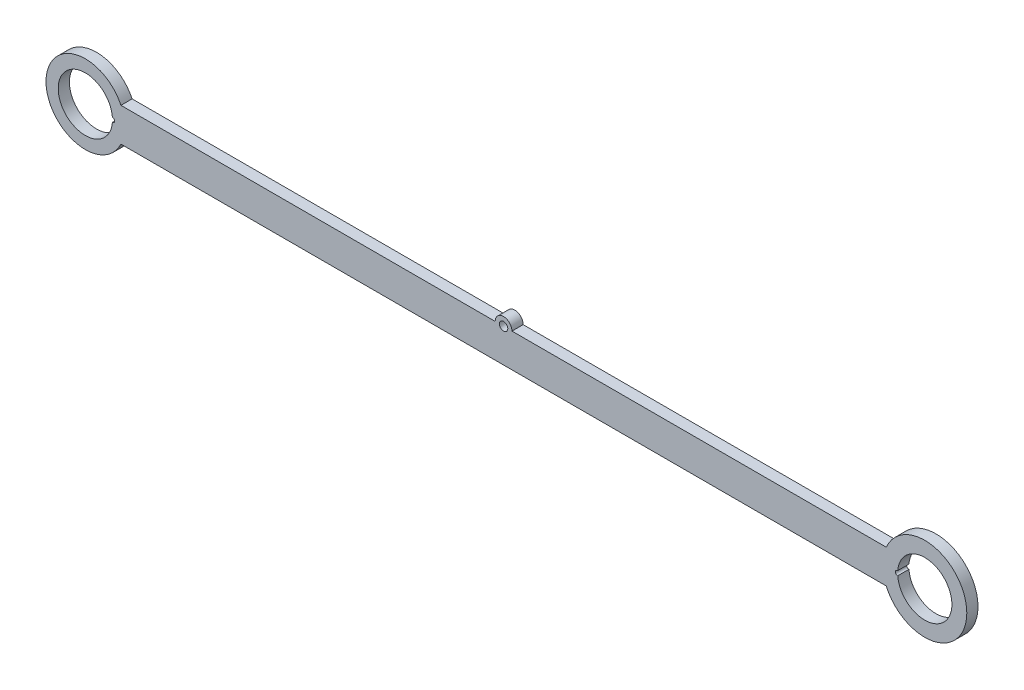
SolidWorks part; units mm, degrees
ref_plane "前视基准面" through (0, 0, 0) normal (0, 0, 1) x (1, 0, 0)
ref_plane "上视基准面" through (0, 0, 0) normal (0, 1, 0) x (1, 0, 0)
ref_plane "右视基准面" through (0, 0, 0) normal (1, 0, 0) x (0, 0, -1)
sketch "草图1" plane through (0, 0, 0) normal (0, 0, 1) x (1, 0, 0)
  line L0 (0, 0) -> (300, 0) construction
  line L1 (12.7187, 6) -> (286.2245, 6)
  line L2 (35.8014, 6) -> (35.8014, 0) construction
  line L3 (12.7187, -6) -> (286.2245, -6)
  line L4 (35.8014, 0) -> (35.8014, -6) construction
  circle A0 centre (0, 0) radius 9.7
  circle A1 centre (300, 0) radius 9.7
  circle A2 centre (0, 0) radius 14.0629 construction
  circle A3 centre (300, 0) radius 15.0255 construction
  arc A4 (12.7187, -6) -> (12.7187, 6) centre (0, 0) cw
  arc A5 (286.2245, -6) -> (286.2245, 6) centre (300, 0) ccw
  dimension "D1" = 19.4
  dimension "D3" = 6
  dimension "D2" = 300
extrude "凸台-拉伸1" add sketch "草图1" along normal blind 4 contours L3 A5 L1 A4
sketch "草图3" plane through (0, 0, 4) normal (0, 0, 1) x (1, 0, 0)
  circle A0 centre (9.7, 0) radius 0.8
  circle A1 centre (0, 0) radius 9.7 construction
  circle A2 centre (290.3, 0) radius 0.8
  circle A3 centre (300, 0) radius 9.7 construction
extrude "切除-拉伸1" cut sketch "草图3" against normal blind 10
sketch "草图4" plane through (0, 0, 4) normal (0, 0, 1) x (1, 0, 0)
  line L0 (286.2245, 6) -> (12.7187, 6) construction
  circle A0 centre (149.4716, 6) radius 3
extrude "凸台-拉伸2" add sketch "草图4" against normal blind 4 contours A0
sketch "草图5" plane through (0, 0, 4) normal (0, 0, 1) x (1, 0, 0)
  circle A0 centre (149.4716, 6) radius 1.5
extrude "切除-拉伸2" cut sketch "草图5" against normal blind 4
